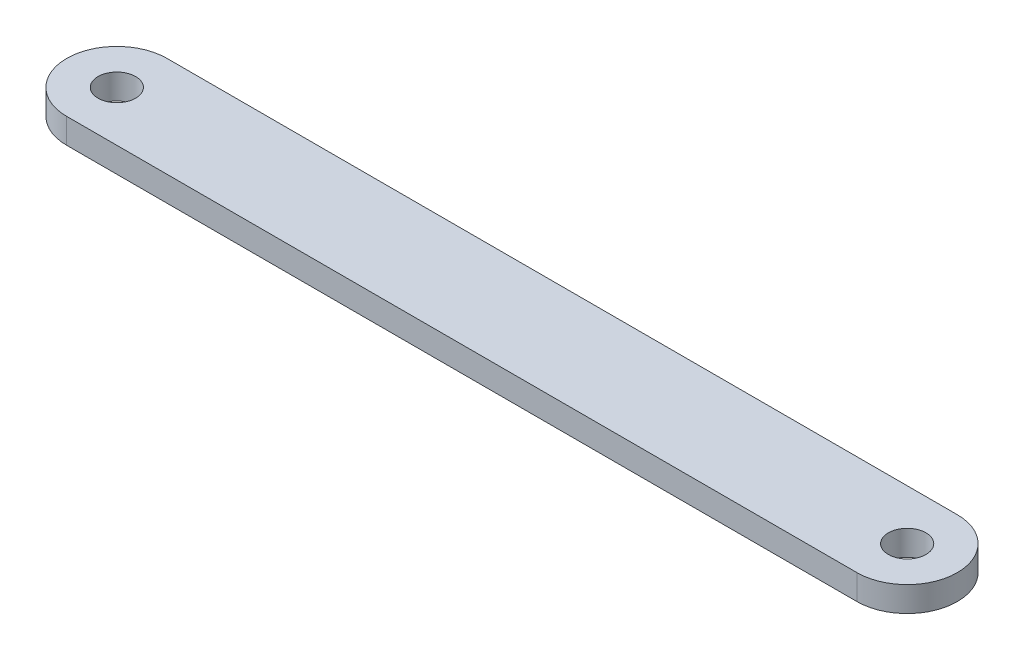
SolidWorks part; units mm, degrees
ref_plane "Plan de face" through (0, 0, 0) normal (0, 0, 1) x (1, 0, 0)
ref_plane "Plan de dessus" through (0, 0, 0) normal (0, 1, 0) x (1, 0, 0)
ref_plane "Plan de droite" through (0, 0, 0) normal (1, 0, 0) x (0, 0, -1)
sketch "Esquisse1" plane through (0, 0, 0) normal (0, 1, 0) x (1, 0, 0)
  line L0 (0, 0) -> (63, 0) construction
  line L1 (0, 4) -> (63, 4)
  line L2 (0, -4) -> (63, -4)
  arc A0 (0, 4) -> (0, -4) centre (0, 0) ccw
  arc A1 (63, -4) -> (63, 4) centre (63, 0) ccw
  circle A2 centre (0, 0) radius 1.5
  circle A3 centre (63, 0) radius 1.5
  point P3 (31.5, 0)
  dimension "D1" = 3
  dimension "D2" = 8
  dimension "D3" = 63
extrude "Boss.-Extru.1" add sketch "Esquisse1" along normal blind 2
